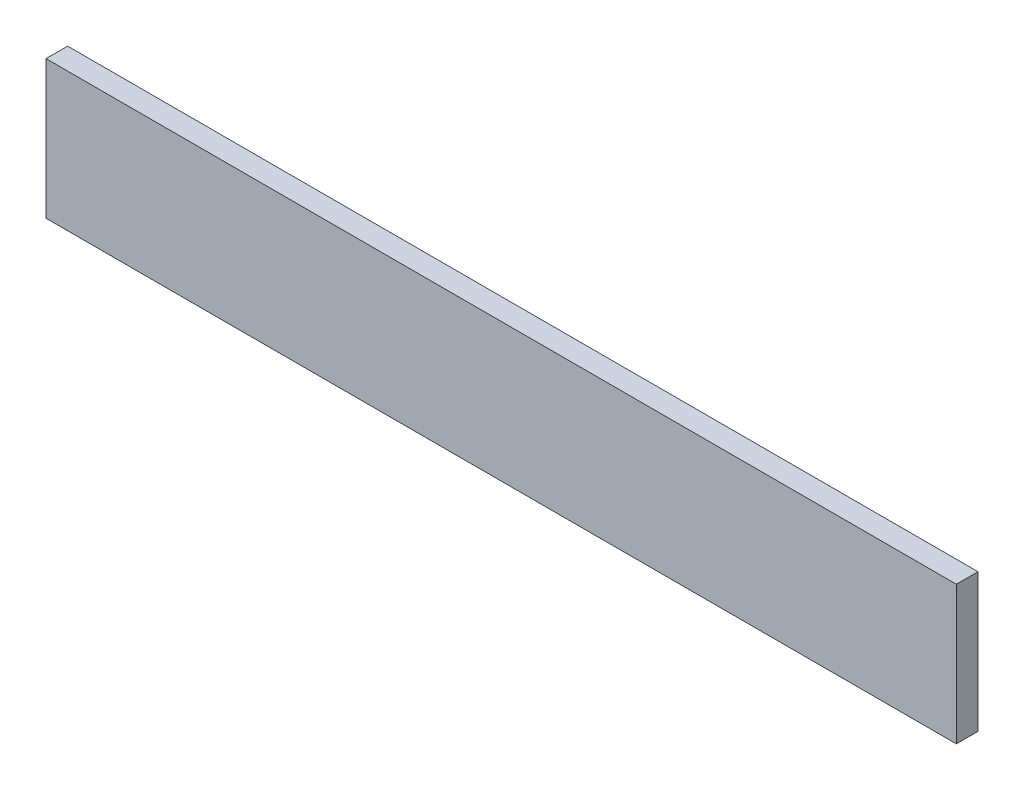
SolidWorks part; units mm, degrees
material "Roble"
ref_plane "Alzado" through (0, 0, 0) normal (0, 0, 1) x (1, 0, 0)
ref_plane "Planta" through (0, 0, 0) normal (0, 1, 0) x (1, 0, 0)
ref_plane "Vista lateral" through (0, 0, 0) normal (1, 0, 0) x (0, 0, -1)
sketch "Croquis1" plane through (0, 0, 0) normal (0, 0, 1) x (1, 0, 0)
  line L1 (-378.575, -57.5) -> (378.575, -57.5)
  line L2 (-378.575, -57.5) -> (-378.575, 57.5)
  line L3 (-378.575, 57.5) -> (378.575, 57.5)
  line L4 (378.575, -57.5) -> (378.575, 57.5)
  line L5 (-378.575, -57.5) -> (378.575, 57.5) construction
  line L6 (-378.575, 57.5) -> (378.575, -57.5) construction
  point P0 (0, 0)
  dimension "D1" = 115
  dimension "D2" = 757.15
extrude "Saliente-Extruir1" add sketch "Croquis1" along normal blind 18
